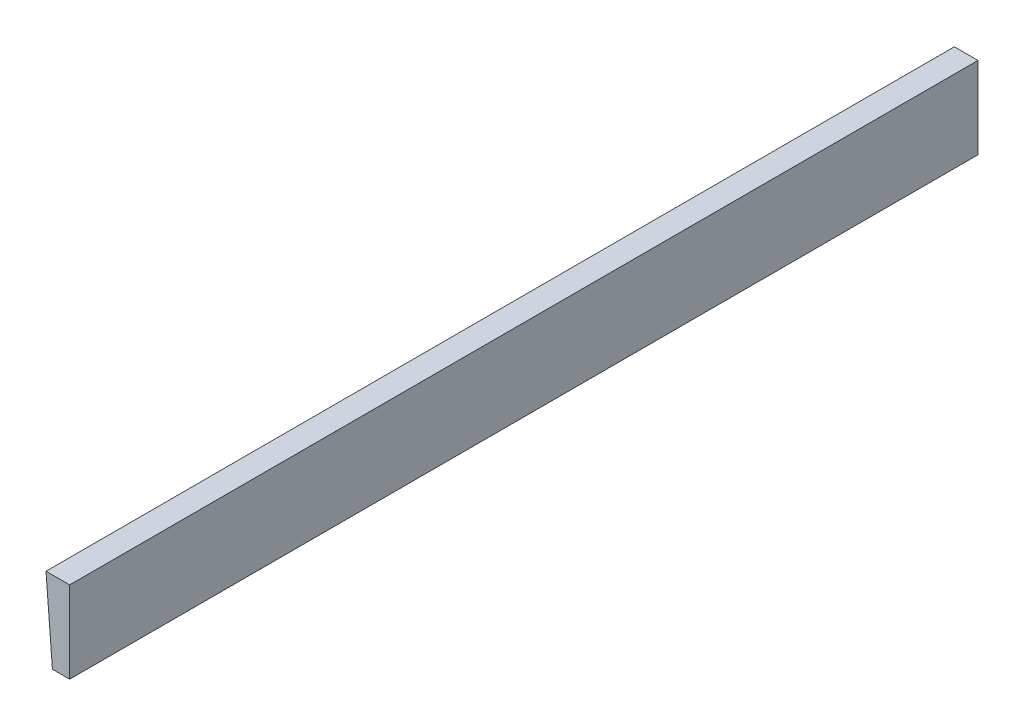
SolidWorks part; units mm, degrees
material "PET"
ref_plane "Front Plane" through (0, 0, 0) normal (0, 0, 1) x (1, 0, 0)
ref_plane "Top Plane" through (0, 0, 0) normal (0, 1, 0) x (1, 0, 0)
ref_plane "Right Plane" through (0, 0, 0) normal (1, 0, 0) x (0, 0, -1)
sketch "Sketch1" plane through (0, 0, 0) normal (0, 0, 1) x (1, 0, 0)
  line L2 (-5, 10) -> (-4.213, 0)
  line L3 (-4.213, 0) -> (0, 0)
  line L4 (0, 0) -> (0, 10)
  line L6 (-5.787, 20) -> (-5, 10)
  line L9 (0, 20) -> (-5.787, 20)
  line L10 (0, 10) -> (0, 20)
  dimension "D1" = 5
  dimension "D2" = 4.5
  dimension "D3" = 10
  dimension "D4" = 10
extrude "Boss-Extrude1" add sketch "Sketch1" against normal mid plane 222.375
